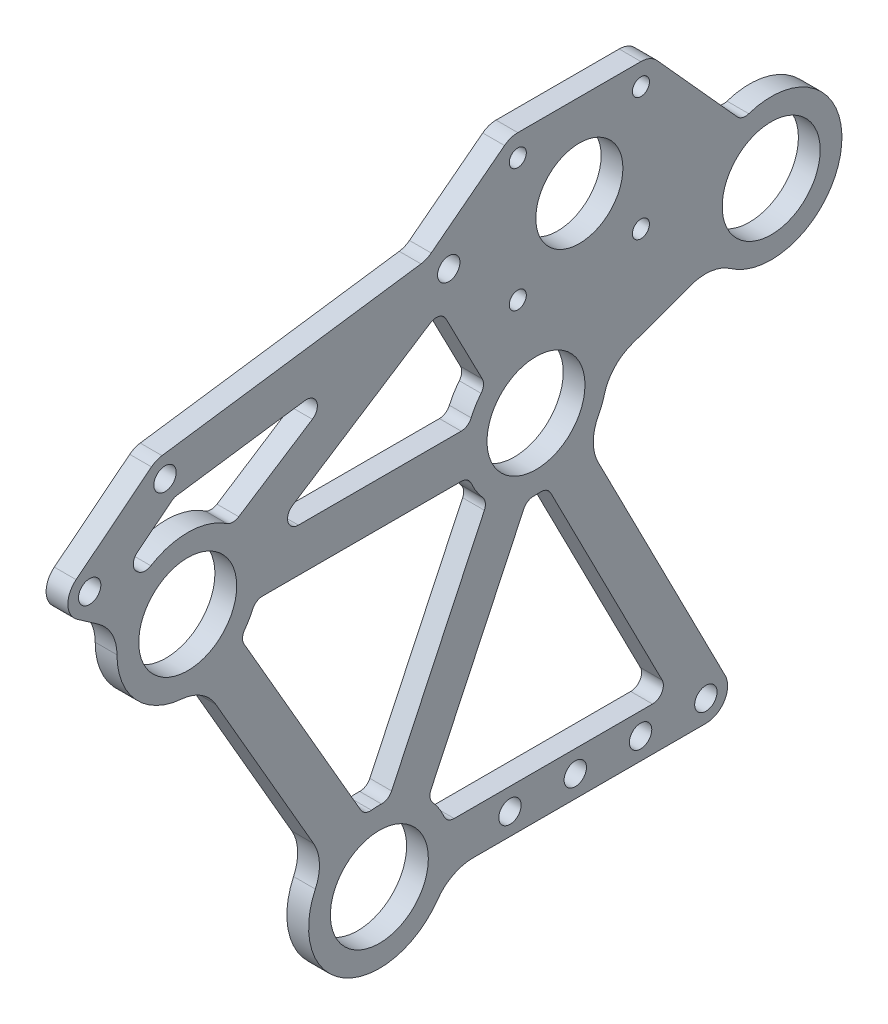
SolidWorks part; units mm, degrees
material "6061-T6 (SS)"
ref_plane "Front Plane" through (0, 0, 0) normal (0, 0, 1) x (1, 0, 0)
ref_plane "Top Plane" through (0, 0, 0) normal (0, 1, 0) x (1, 0, 0)
ref_plane "Right Plane" through (0, 0, 0) normal (1, 0, 0) x (0, 0, -1)
sketch "Sketch1" plane through (0, 0, 0) normal (1, 0, 0) x (0, 0, -1)
  line L0 (-944.9092, 463.0161) -> (-889, 366.1786) construction
  line L1 (-889, 366.1786) -> (-793.75, 366.1786) construction
  line L2 (-793.75, 366.1786) -> (-843.3092, 463.0161) construction
  line L3 (-843.3092, 463.0161) -> (-774.7, 488.0385) construction
  line L4 (-774.7, 488.0385) -> (-868.7603, 512.2162) construction
  line L5 (-868.7603, 512.2162) -> (-951.5252, 500.5373) construction
  line L6 (-951.5252, 500.5373) -> (-973.518, 483.0483) construction
  line L7 (-973.518, 483.0483) -> (-944.9092, 463.0161) construction
  line L8 (-977.1603, 477.8466) -> (-949.7045, 458.6219)
  line L9 (-949.7045, 458.6219) -> (-892.6662, 359.8286)
  line L10 (-892.6662, 359.8286) -> (-793.75, 359.8286)
  line L11 (-788.0973, 369.0715) -> (-834.3828, 459.5125)
  line L12 (-834.3828, 459.5125) -> (-753.2839, 489.09)
  line L14 (-876.8621, 517.4858) -> (-952.4124, 506.825)
  line L15 (-955.4774, 505.5074) -> (-977.4703, 488.0184)
  line L16 (-892.6662, 359.8286) -> (-783.3669, 359.8286) construction
  line L17 (-783.3669, 359.8286) -> (-834.3828, 459.5125) construction
  line L18 (-753.2839, 489.09) -> (-868.3999, 518.6799) construction
  line L19 (-868.3999, 518.6799) -> (-954.1243, 506.5834) construction
  line L20 (-954.1243, 506.5834) -> (-984.1271, 482.7248) construction
  line L21 (-984.1271, 482.7248) -> (-949.7045, 458.6219) construction
  line L22 (-868.7603, 512.2162) -> (-848.6209, 530.1767) construction
  line L23 (-848.6209, 530.1767) -> (-812.6998, 530.1767) construction
  line L24 (-812.6998, 530.1767) -> (-774.7, 488.0385) construction
  line L25 (-873.8748, 518.7426) -> (-852.4954, 535.2076)
  line L26 (-848.6209, 536.5267) -> (-812.6998, 536.5267)
  line L27 (-807.9841, 534.4293) -> (-769.9843, 492.2911)
  line L28 (-872.9868, 516.9553) -> (-851.041, 536.5267) construction
  line L29 (-851.041, 536.5267) -> (-809.8755, 536.5267) construction
  line L30 (-809.8755, 536.5267) -> (-769.9843, 492.2911) construction
  circle A0 centre (-774.7, 488.0385) radius 14.2875 construction
  circle A1 centre (-850.9, 366.1786) radius 3.2639 construction
  circle A2 centre (-793.75, 366.1786) radius 3.2639 construction
  circle A3 centre (-812.8, 366.1786) radius 3.2639 construction
  circle A4 centre (-831.85, 366.1786) radius 3.2639 construction
  circle A5 centre (-973.518, 483.0483) radius 3.2639 construction
  circle A6 centre (-951.5252, 500.5373) radius 3.2639 construction
  circle A7 centre (-868.7603, 512.2162) radius 3.2639 construction
  circle A8 centre (-889, 366.1786) radius 14.2875 construction
  circle A9 centre (-843.3092, 463.0161) radius 14.2875 construction
  circle A10 centre (-944.9092, 463.0161) radius 14.2875 construction
  circle A11 centre (-774.7, 488.0385) radius 14.2875
  circle A12 centre (-850.9, 366.1786) radius 3.2639
  circle A13 centre (-793.75, 366.1786) radius 3.2639
  circle A14 centre (-812.8, 366.1786) radius 3.2639
  circle A15 centre (-831.85, 366.1786) radius 3.2639
  circle A16 centre (-973.518, 483.0483) radius 3.2639
  circle A17 centre (-951.5252, 500.5373) radius 3.2639
  circle A18 centre (-868.7603, 512.2162) radius 3.2639
  circle A19 centre (-889, 366.1786) radius 14.2875
  circle A20 centre (-843.3092, 463.0161) radius 14.2875
  circle A21 centre (-944.9092, 463.0161) radius 14.2875
  circle A22 centre (-944.9092, 463.0161) radius 20.6375
  circle A23 centre (-843.3092, 463.0161) radius 20.6375
  circle A24 centre (-889, 366.1786) radius 20.6375
  circle A25 centre (-774.7, 488.0385) radius 20.6375
  arc A26 (-793.75, 359.8286) -> (-788.0973, 369.0715) centre (-793.75, 366.1786) ccw
  arc A28 (-952.4124, 506.825) -> (-955.4774, 505.5074) centre (-951.5252, 500.5373) ccw
  arc A29 (-977.1603, 477.8466) -> (-977.4703, 488.0184) centre (-973.518, 483.0483) cw
  circle A30 centre (-848.6209, 530.1767) radius 2.4892 construction
  circle A31 centre (-812.6998, 530.1767) radius 2.4892 construction
  circle A32 centre (-812.6998, 494.2557) radius 2.4892 construction
  circle A33 centre (-848.6209, 494.2557) radius 2.4892 construction
  circle A34 centre (-848.6209, 530.1767) radius 2.4892
  circle A35 centre (-812.6998, 530.1767) radius 2.4892
  circle A36 centre (-812.6998, 494.2557) radius 2.4892
  circle A37 centre (-848.6209, 494.2557) radius 2.4892
  arc A38 (-812.6998, 536.5267) -> (-807.9841, 534.4293) centre (-812.6998, 530.1767) cw
  arc A39 (-852.4954, 535.2076) -> (-848.6209, 536.5267) centre (-848.6209, 530.1767) cw
  arc A40 (-876.8621, 517.4858) -> (-873.8748, 518.7426) centre (-877.7493, 523.7736) ccw
  circle A41 centre (-830.6603, 512.2162) radius 12.7 construction
  circle A42 centre (-830.6603, 512.2162) radius 12.7
  dimension "D4" = 6.35
  dimension "D6" = 6.35
  dimension "D1" = 6.35
  dimension "D5" = 6.35
  dimension "D2" = 6.35
  dimension "D3" = 6.35
extrude "Boss-Extrude1" add sketch "Sketch1" along normal blind 6.35
fillet "Fillet1" radius 12.7 7 edges at (3.175, 448.4289, 828.7105) (3.175, 475.3448, 790.972) (3.175, 463.7785, 822.6857) (3.175, 359.8286, 869.3637) (3.175, 380.0091, 904.3174) (3.175, 442.8356, 940.5903) (3.175, 469.0774, 964.6365)
sketch "Sketch2" plane through (6.35, 0, 0) normal (1, 0, 0) x (0, 0, -1)
  line L0 (-944.9092, 463.0161) -> (-843.3092, 463.0161) construction
  line L1 (-843.3092, 463.0161) -> (-868.7603, 512.2162) construction
  line L2 (-868.7603, 512.2162) -> (-944.9092, 463.0161) construction
  line L3 (-906.8348, 487.6161) -> (-951.5252, 500.5373) construction
  line L4 (-951.5252, 500.5373) -> (-868.7603, 512.2162) construction
  line L5 (-951.5252, 500.5373) -> (-973.518, 483.0483) construction
  line L6 (-973.518, 483.0483) -> (-944.9092, 463.0161) construction
  line L7 (-950.6379, 494.2496) -> (-867.8731, 505.9285)
  line L8 (-955.4774, 505.5074) -> (-984.1271, 482.7248)
  line L9 (-984.1271, 482.7248) -> (-948.5514, 457.8145)
  line L10 (-905.071, 493.7163) -> (-949.7614, 506.6374)
  line L11 (-872.2064, 517.5498) -> (-948.3552, 468.3497)
  line L12 (-944.9092, 456.6661) -> (-832.875, 456.6661)
  line L13 (-832.875, 456.6661) -> (-863.1203, 515.1338)
  line L14 (-952.4124, 506.825) -> (-869.6476, 518.5039)
  line L15 (-947.5729, 495.5672) -> (-962.909, 483.3717)
  line L16 (-962.909, 483.3717) -> (-941.2669, 468.2177)
  line L17 (-908.5985, 481.516) -> (-953.2889, 494.4371)
  line L18 (-865.3143, 506.8826) -> (-941.4631, 457.6825)
  line L19 (-944.9092, 469.3661) -> (-853.7433, 469.3661)
  line L20 (-853.7433, 469.3661) -> (-874.4004, 509.2986)
  line L21 (-944.9092, 463.0161) -> (-889, 366.1786) construction
  line L22 (-889, 366.1786) -> (-843.3092, 463.0161) construction
  line L23 (-843.3092, 463.0161) -> (-793.75, 366.1786) construction
  line L24 (-793.75, 366.1786) -> (-889, 366.1786) construction
  line L25 (-950.4084, 459.8411) -> (-894.4993, 363.0036)
  line L26 (-899.0175, 359.8286) -> (-843.5406, 477.4066)
  line L27 (-843.5406, 477.4066) -> (-783.3669, 359.8286)
  line L28 (-783.3669, 359.8286) -> (-899.0175, 359.8286)
  line L29 (-939.4099, 466.1911) -> (-883.5007, 369.3536)
  line L30 (-878.9825, 372.5286) -> (-843.0777, 448.6256)
  line L31 (-843.0777, 448.6256) -> (-804.1331, 372.5286)
  line L32 (-804.1331, 372.5286) -> (-878.9825, 372.5286)
  line L33 (-905.0741, 481.1936) -> (-914.3384, 475.2079)
  circle A0 centre (-973.518, 483.0483) radius 6.35
  circle A1 centre (-951.5252, 500.5373) radius 6.35
  circle A2 centre (-944.9092, 463.0161) radius 20.6375
  circle A3 centre (-868.7603, 512.2162) radius 6.35
  circle A4 centre (-843.3092, 463.0161) radius 20.6375
  circle A5 centre (-889, 366.1786) radius 20.6375
  arc A6 (-914.3384, 475.2079) -> (-912.6154, 469.3661) centre (-912.6154, 472.5411) ccw
  point P55 (-905.0741, 481.1936)
  dimension "D1" = 41.275
  dimension "D2" = 12.7
  dimension "D7" = 3.175
  dimension "D5" = 6.35
  dimension "D3" = 6.35
  dimension "D4" = 6.35
  dimension "D6" = 6.35
extrude "Cut-Extrude1" cut sketch "Sketch2" against normal through all contours A2 L11 L17 L15 L16 | L11 L7 L10 | A4 L20 L18 A2 L19 | A5 L26 A4 L12 A2 L29 | A5 L32 L31 A4 L30 | L17 L11 L10 L7 L15
fillet "Fillet2" radius 3.175 20 edges at (3.175, 372.5286, 804.1331) (3.175, 442.5477, 845.9454) (3.175, 442.643, 840.016) (3.175, 447.967, 857.4311) (3.175, 456.6661, 862.9454) (3.175, 381.2277, 874.878) (3.175, 372.5286, 869.3637) (3.175, 386.647, 886.3637) (3.175, 386.3591, 893.3189) (3.175, 456.6661, 925.2729) (3.175, 449.1856, 929.5918) (3.175, 494.4911, 948.926) (3.175, 483.3717, 962.909) (3.175, 479.4806, 957.3521) (3.175, 479.006, 931.862) (3.175, 501.8988, 896.43) (3.175, 503.0878, 871.1876) (3.175, 469.3661, 862.9454) (3.175, 477.5394, 857.9714) (3.175, 506.8736, 783.1347)
